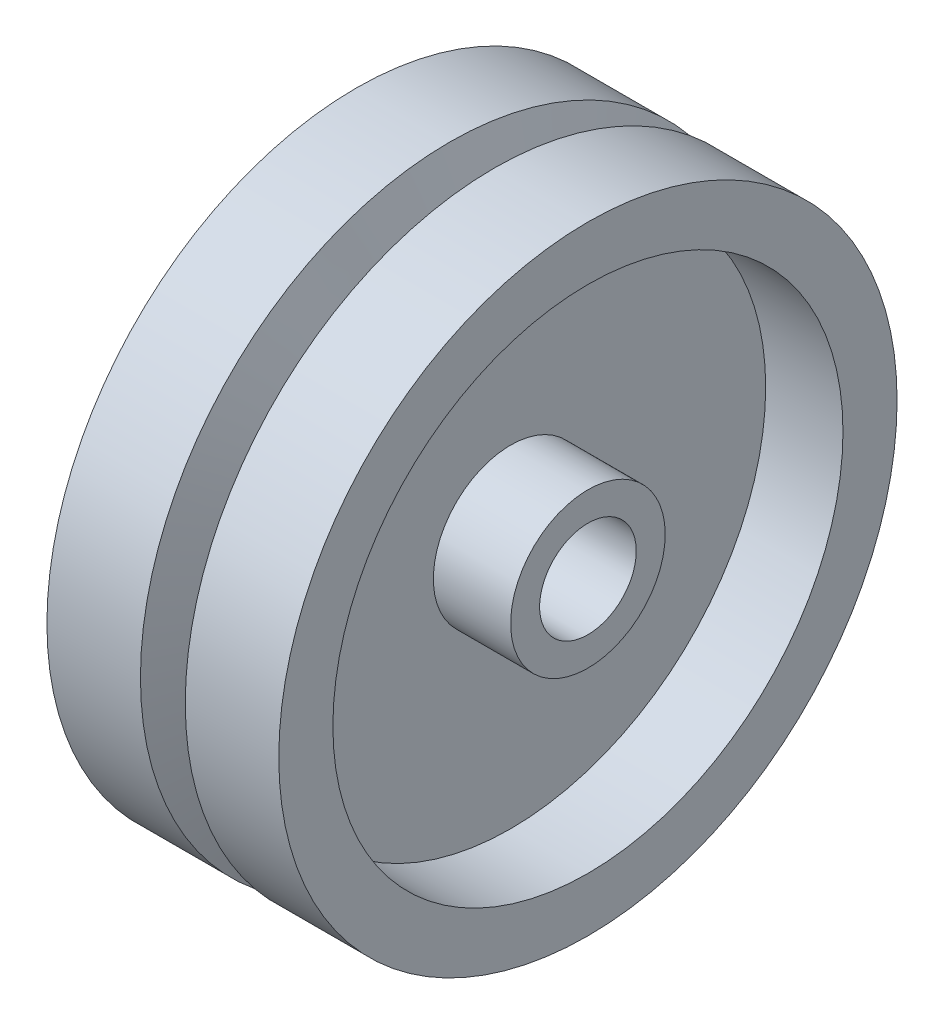
SolidWorks part; units mm, degrees
ref_plane "Front Plane" through (0, 0, 0) normal (0, 0, 1) x (1, 0, 0)
ref_plane "Top Plane" through (0, 0, 0) normal (0, 1, 0) x (1, 0, 0)
ref_plane "Right Plane" through (0, 0, 0) normal (1, 0, 0) x (0, 0, -1)
sketch "Sketch1" plane through (0, 0, 0) normal (0, 0, 1) x (1, 0, 0)
  line L0 (0, 0) -> (-9261.4508, 0) construction
  line L1 (0, 0) -> (0, -9261.4508) construction
  line L2 (-7.5, 3.125) -> (7.5, 3.125)
  line L3 (7.5, 3.125) -> (7.5, 5)
  line L4 (7.5, 5) -> (2.5, 5)
  line L5 (2.5, 5) -> (2.5, 16.5)
  line L6 (2.5, 16.5) -> (7.5, 16.5)
  line L7 (7.5, 16.5) -> (7.5, 20)
  line L8 (7.5, 20) -> (1.4497, 20)
  line L9 (1.4497, 20) -> (0, 16.5)
  line L10 (-7.5, 20) -> (-1.4497, 20)
  line L11 (-7.5, 16.5) -> (-7.5, 20)
  line L12 (-2.5, 16.5) -> (-7.5, 16.5)
  line L13 (-2.5, 5) -> (-2.5, 16.5)
  line L14 (-7.5, 5) -> (-2.5, 5)
  line L15 (-7.5, 3.125) -> (-7.5, 5)
  line L16 (-1.4497, 20) -> (0, 16.5)
  point P8 (0, 3.125)
  dimension "D1" = 3.125
  dimension "D2" = 5
  dimension "D3" = 16.5
  dimension "D4" = 20
  dimension "D5" = 2.5
  dimension "D6" = 7.5
  dimension "D7" = 7.5
  dimension "D8" = 22.5
revolve "Revolve1" add sketch "Sketch1" angle 360 about L0
